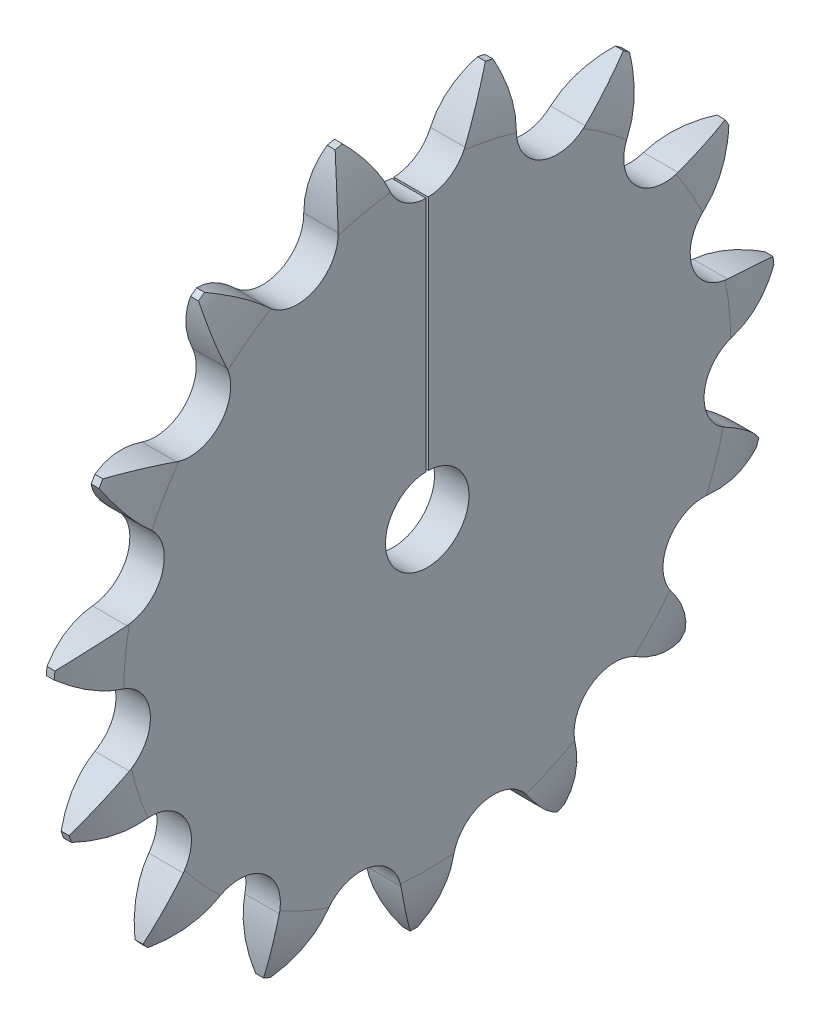
SolidWorks part; units mm, degrees
material "Barra Redonda SAE 1020 - 2\""
ref_plane "Plano frontal" through (0, 0, 0) normal (0, 0, 1) x (1, 0, 0)
ref_plane "Plano superior" through (0, 0, 0) normal (0, 1, 0) x (1, 0, 0)
ref_plane "Plano direito" through (0, 0, 0) normal (1, 0, 0) x (0, 0, -1)
sketch "Esboço1" plane through (0, 0, 0) normal (0, 1, 0) x (1, 0, 0)
  line L0 (24.686, 0) -> (94.686, 0) construction
  line L1 (0, 0) -> (0, 29.0642)
  line L2 (0, 0) -> (3.3, 0)
  line L3 (3.3, 0) -> (3.3, 29.0642)
  line L4 (2.03, 34.6) -> (1.27, 34.6)
  arc A0 (0, 29.0642) -> (1.27, 34.6) centre (12.7, 29.0642) cw
  arc A1 (3.3, 29.0642) -> (2.03, 34.6) centre (-9.4, 29.0642) ccw
  dimension "D4" = 12.7
  dimension "D1" = 1.27
  dimension "D2" = 1.27
  dimension "D3" = 3.3
  dimension "D5" = 69.2
revolve "Revolução1" add sketch "Esboço1" angle 360 about L0
sketch "Esboço2" plane through (3.3, 0, 0) normal (1, 0, 0) x (0, 0, -1)
  line L0 (0, 30.5806) -> (3.6026, 29.0513) construction
  line L1 (0, 0) -> (0, 79.7127) construction
  line L2 (0, 30.5806) -> (-10, 30.5806) construction
  line L3 (0, 30.5806) -> (-3.6026, 29.0513) construction
  arc A0 (3.6026, 29.0513) -> (7.2734, 34.3425) centre (18.1558, 22.8739) cw
  arc A1 (3.6026, 29.0513) -> (-3.6026, 29.0513) centre (0, 30.5806) cw
  arc A2 (-3.6026, 29.0513) -> (-7.2734, 34.3425) centre (-18.1558, 22.8739) ccw
  arc A3 (7.2734, 34.3425) -> (-7.2734, 34.3425) centre (0, 0) ccw
  dimension "D2" = 3.9137
  dimension "D4" = 15.81
  dimension "D5" = 35.1043
  dimension "D1" = 30.5806
  dimension "D3" = 134
extrude "Corte-extrusão1" cut sketch "Esboço2" against normal through all
pattern_circular "PadrãoCircular1" count 15 over 360 about axis through (0, 0, 0) along (1, 0, 0) of "Corte-extrusão1"
sketch "Esboço3" plane through (3.3, 0, 0) normal (1, 0, 0) x (0, 0, -1)
  circle A0 centre (0, 0) radius 4
  dimension "D1" = 8
extrude "Corte-extrusão2" cut sketch "Esboço3" against normal through all
sketch "Esboço4" plane through (0, 0, 0) normal (-1, 0, 0) x (0, 0, 1)
  line L0 (0, 0) -> (0, 32.0392) construction
  line L1 (-0.1, 0) -> (0.1, 0)
  line L2 (-0.1, 0) -> (-0.1, 30)
  line L3 (-0.1, 30) -> (0.1, 30)
  line L4 (0.1, 0) -> (0.1, 30)
  dimension "D1" = 30
  dimension "D2" = 0.2
extrude "Corte-extrusão3" cut sketch "Esboço4" against normal blind 10
